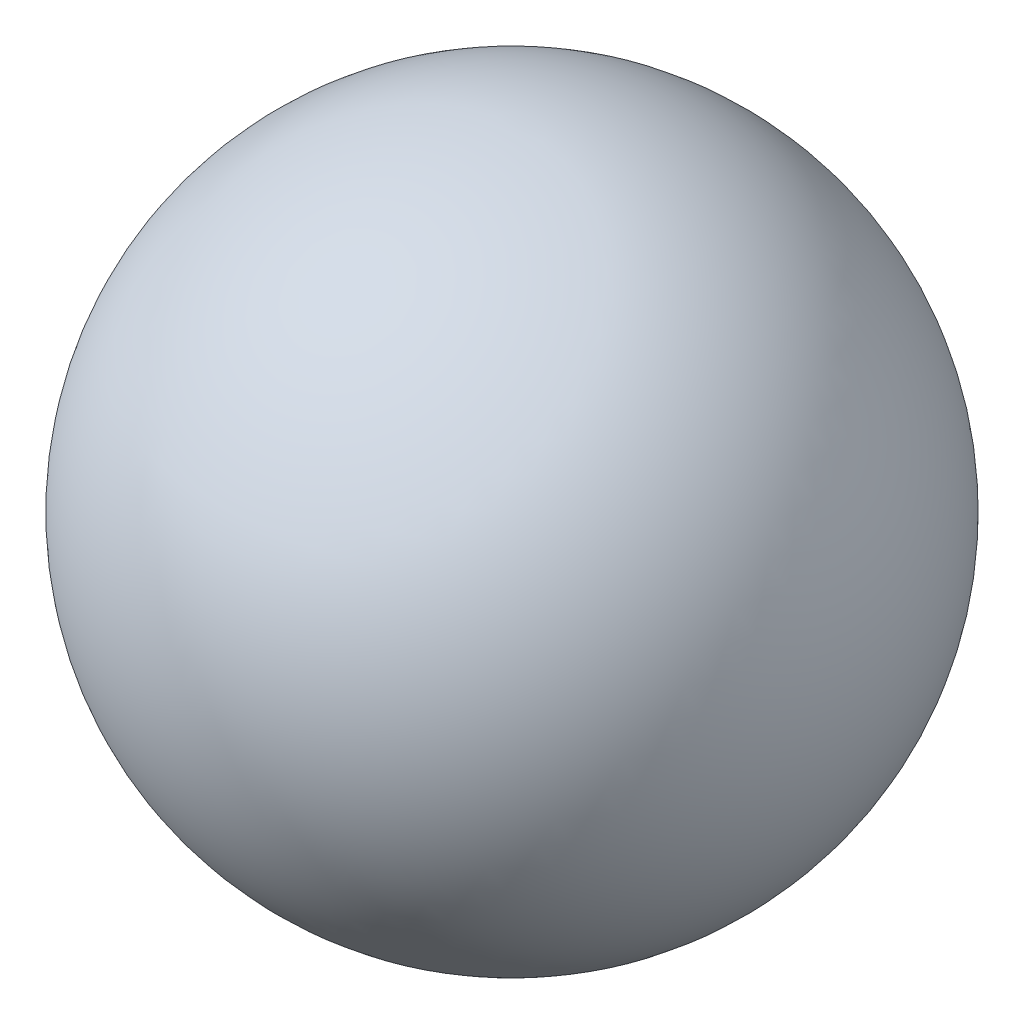
SolidWorks part; units mm, degrees
ref_plane "前视基准面" through (0, 0, 0) normal (0, 0, 1) x (1, 0, 0)
ref_plane "上视基准面" through (0, 0, 0) normal (0, 1, 0) x (1, 0, 0)
ref_plane "右视基准面" through (0, 0, 0) normal (1, 0, 0) x (0, 0, -1)
sketch "草图1" plane through (0, 0, 0) normal (1, 0, 0) x (0, 0, -1)
  line L0 (0, 100.1) -> (0, 0) construction
  line L1 (0, 0) -> (0, -100.1) construction
  line L2 (0, 100.1) -> (0, -100.1)
  line L3 (0, 100.1) -> (0, -100.1)
  arc A0 (0, 100.1) -> (0, -100.1) centre (0, 0) ccw
  dimension "D1" = 200.2
revolve "旋转8" add sketch "草图1" angle 360 about L0
